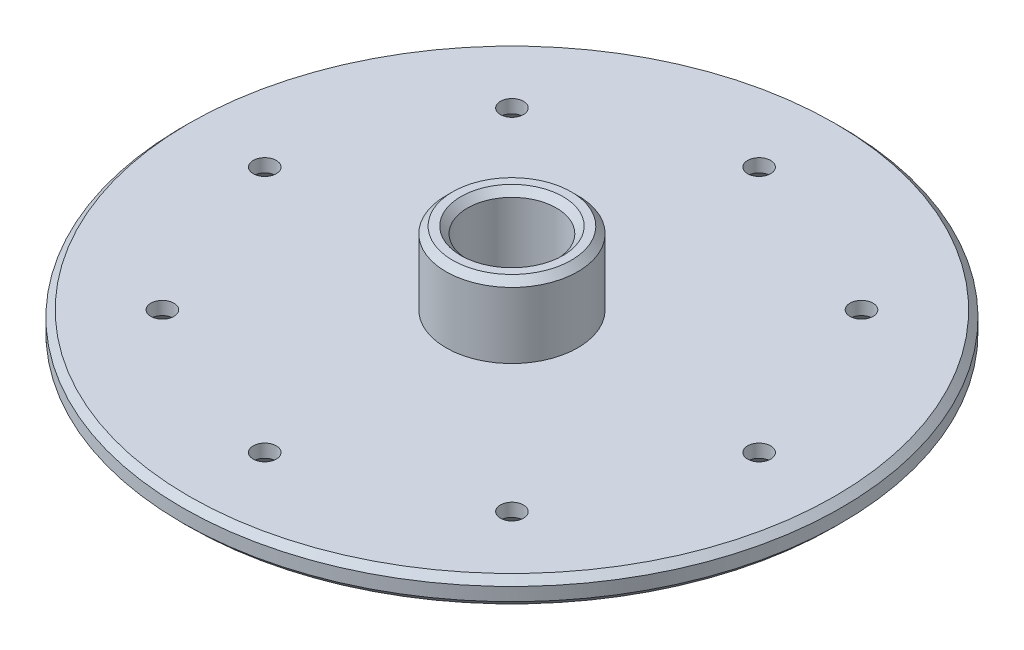
SolidWorks part; units mm, degrees
ref_plane "Front Plane" through (0, 0, 0) normal (0, 0, 1) x (1, 0, 0)
ref_plane "Top Plane" through (0, 0, 0) normal (0, 1, 0) x (1, 0, 0)
ref_plane "Right Plane" through (0, 0, 0) normal (1, 0, 0) x (0, 0, -1)
sketch "Sketch1" plane through (0, 0, 0) normal (1, 0, 0) x (0, 0, -1)
  line L0 (0, 143.3077) -> (0, -115.2692) construction
  line L1 (-10, 14) -> (-10, 4)
  line L2 (-10, 4) -> (-49, 4)
  line L3 (-50, 3) -> (-50, 1)
  line L4 (-49, 0) -> (-19, 0)
  line L5 (-18, -1) -> (-18, -14)
  line L6 (-17, -15) -> (-15.25, -15)
  line L7 (-14.25, -14) -> (-14.25, -5.1)
  line L8 (-14.25, -5) -> (-6.75, -5) construction
  line L9 (-6.75, 0) -> (-6.75, 14)
  line L10 (-7.75, 15) -> (-9, 15)
  line L12 (-6.75, -5) -> (-6.75, 0) construction
  line L13 (-11.75, -5) -> (-14.15, -5)
  line L14 (-11.75, -5) -> (-6.75, 0)
  line L15 (-15.25, -15) -> (-14.25, -14)
  line L16 (-18, -14) -> (-17, -15)
  line L17 (-19, 0) -> (-18, -1)
  line L18 (-14.25, -5.1) -> (-14.15, -5)
  line L19 (-50, 1) -> (-49, 0)
  line L20 (-49, 4) -> (-50, 3)
  line L21 (-9, 15) -> (-10, 14)
  line L22 (-6.75, 14) -> (-7.75, 15)
  point P3 (-10, 15)
  point P6 (-50, 4)
  point P7 (-50, 0)
  point P8 (-18, 0)
  point P9 (-18, -15)
  point P10 (-14.25, -15)
  point P13 (-6.75, 15)
  dimension "D1" = 13.5
  dimension "D2" = 28.5
  dimension "D3" = 30
  dimension "D4" = 4
  dimension "D5" = 36
  dimension "D6" = 100
  dimension "D7" = 20
  dimension "D8" = 10
  dimension "D9" = 15
  dimension "D10" = 2.5
  dimension "D11" = 45
revolve "Revolve1" add sketch "Sketch1" angle 360 about L0
sketch "Sketch2" plane through (0, 4, 0) normal (0, 1, 0) x (1, 0, 0)
  line L0 (0, 0) -> (0, 37.5) construction
  circle A0 centre (0, 0) radius 37.5 construction
  circle A1 centre (0, 37.5) radius 1.75
  circle A2 centre (26.5165, 26.5165) radius 1.75
  circle A3 centre (37.5, 0) radius 1.75
  circle A4 centre (26.5165, -26.5165) radius 1.75
  circle A5 centre (0, -37.5) radius 1.75
  circle A6 centre (-26.5165, -26.5165) radius 1.75
  circle A7 centre (-37.5, 0) radius 1.75
  circle A8 centre (-26.5165, 26.5165) radius 1.75
  point P22 (0, 0)
  dimension "D1" = 75
  dimension "D2" = 3.5
  dimension "D3" = 8
extrude "Cut-Extrude1" cut sketch "Sketch2" against normal through all both and the other way through all
chamfer "Chamfer1" distance 2 angle 45 8 edges at (37.5, 0, -1.75) (26.5165, 0, 24.7665) (0, 0, 35.75) (-26.5165, 0, 24.7665) (-37.5, 0, -1.75) (-26.5165, 0, -28.2665) (26.5165, 0, -28.2665) (0, 0, -39.25)
